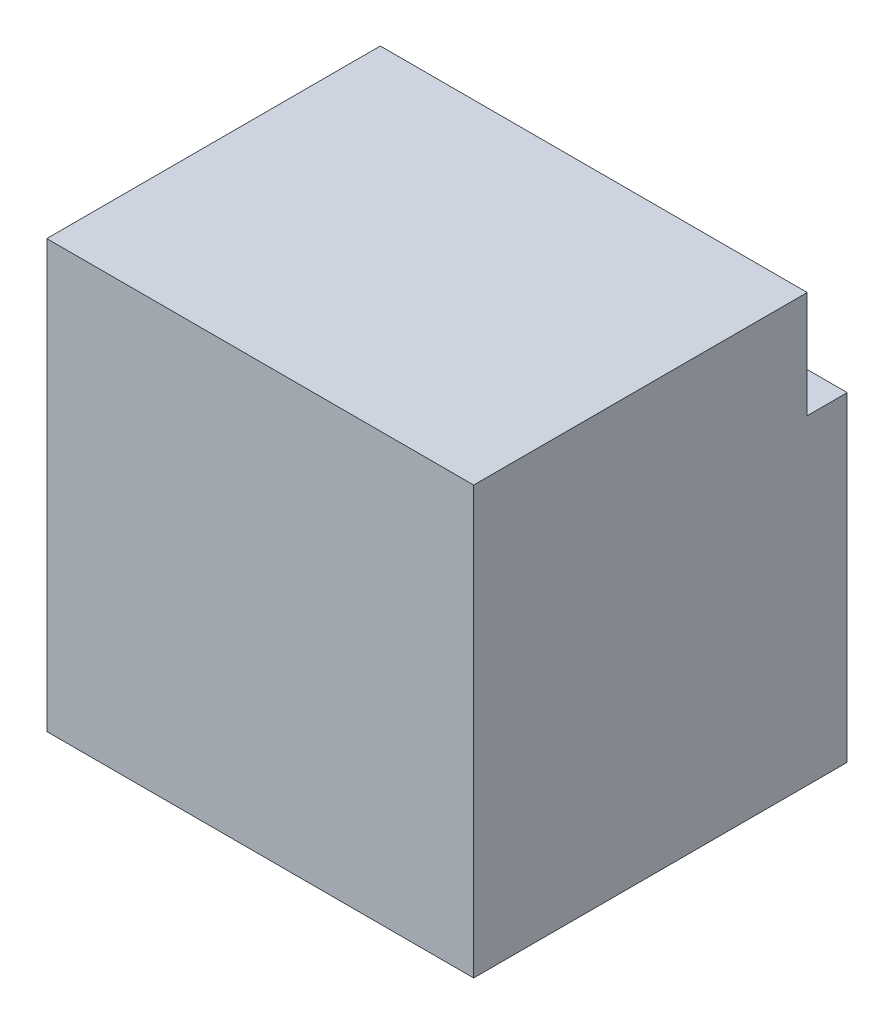
SolidWorks part; units mm, degrees
ref_plane "Ebene vorne" through (0, 0, 0) normal (0, 0, 1) x (1, 0, 0)
ref_plane "Ebene oben" through (0, 0, 0) normal (0, 1, 0) x (1, 0, 0)
ref_plane "Ebene rechts" through (0, 0, 0) normal (1, 0, 0) x (0, 0, -1)
sketch "Skizze1" plane through (0, 0, 0) normal (0, 0, 1) x (1, 0, 0)
  line L1 (-8, 8) -> (8, 8)
  line L2 (-8, 8) -> (-8, -8)
  line L3 (-8, -8) -> (8, -8)
  line L4 (8, 8) -> (8, -8)
  dimension "D1" = 16
  dimension "D2" = 16
  dimension "D3" = 8
  dimension "D4" = 8
extrude "Aufsatz-Linear austragen1" add sketch "Skizze1" along normal blind 14
sketch "Skizze2" plane through (0, -8, 0) normal (0, -1, 0) x (1, 0, 0)
  line L0 (-8, 0) -> (8, 0) construction
  line L1 (-5.5, 10) -> (5.5, 10)
  line L2 (-5.5, 10) -> (-5.5, 3)
  line L3 (-5.5, 3) -> (5.5, 3)
  line L4 (5.5, 10) -> (5.5, 3)
  dimension "D1" = 11
  dimension "D2" = 7
  dimension "D3" = 3
  dimension "D4" = 5.5
extrude "Schnitt-Linear austragen1" cut sketch "Skizze2" against normal blind 10
sketch "Skizze3" plane through (0, -8, 0) normal (0, -1, 0) x (1, 0, 0)
  line L0 (5.5, 10) -> (-5.5, 10) construction
  line L1 (-3.5, 12) -> (3.5, 12)
  line L2 (-3.5, 12) -> (-3.5, 10)
  line L3 (-3.5, 10) -> (3.5, 10)
  line L4 (3.5, 12) -> (3.5, 10)
  dimension "D1" = 2
  dimension "D2" = 7
  dimension "D3" = 3.5
extrude "Schnitt-Linear austragen2" cut sketch "Skizze3" against normal blind 10
sketch "Skizze4" plane through (0, -8, 0) normal (0, -1, 0) x (1, 0, 0)
  line L0 (3.5, 10) -> (3.5, 12) construction
  line L1 (4.1, 12.2) -> (6.1, 12.2)
  line L2 (4.1, 12.2) -> (4.1, 10.6)
  line L3 (4.1, 10.6) -> (6.1, 10.6)
  line L4 (6.1, 12.2) -> (6.1, 10.6)
  line L5 (-6.1, 12.2) -> (-4.1, 12.2)
  line L6 (-6.1, 12.2) -> (-6.1, 10.6)
  line L7 (-6.1, 10.6) -> (-4.1, 10.6)
  line L8 (-4.1, 12.2) -> (-4.1, 10.6)
  line L9 (5.5, 10) -> (3.5, 10) construction
  line L10 (-3.5, 12) -> (-3.5, 10) construction
  dimension "D1" = 2
  dimension "D2" = 1.6
  dimension "D3" = 2
  dimension "D4" = 1.6
  dimension "D5" = 0.6
  dimension "D6" = 0.6
  dimension "D7" = 0.6
extrude "Schnitt-Linear austragen3" cut sketch "Skizze4" against normal blind 15
sketch "Skizze5" plane through (0, 0, 0) normal (0, 0, -1) x (-1, 0, 0)
  line L0 (8, 8) -> (8, -8) construction
  line L1 (-8, 8) -> (8, 8)
  line L2 (-8, 8) -> (-8, 4)
  line L3 (-8, 4) -> (8, 4)
  line L4 (8, 8) -> (8, 4)
  dimension "D1" = 4
extrude "Schnitt-Linear austragen5" cut sketch "Skizze5" against normal blind 1.5
sketch "Skizze6" plane through (0, 0, 1.5) normal (0, 0, -1) x (-1, 0, 0)
  line L0 (8, 8) -> (-8, 8) construction
  line L1 (-6.5, 7.5) -> (-4.5, 7.5)
  line L2 (-6.5, 7.5) -> (-6.5, 5.5)
  line L3 (-6.5, 5.5) -> (-4.5, 5.5)
  line L4 (-4.5, 7.5) -> (-4.5, 5.5)
  line L5 (4.5, 7.5) -> (6.5, 7.5)
  line L6 (4.5, 7.5) -> (4.5, 5.5)
  line L7 (4.5, 5.5) -> (6.5, 5.5)
  line L8 (6.5, 7.5) -> (6.5, 5.5)
  line L9 (8, 4) -> (8, 8) construction
  line L10 (-8, 8) -> (-8, 4) construction
  dimension "D1" = 2
  dimension "D2" = 2
  dimension "D3" = 2
  dimension "D4" = 2
  dimension "D5" = 0.5
  dimension "D6" = 1.5
  dimension "D7" = 0.5
  dimension "D8" = 1.5
extrude "Schnitt-Linear austragen6" cut sketch "Skizze6" against normal blind 11.5
sketch "Skizze7" plane through (0, 0, 0) normal (0, 0, -1) x (-1, 0, 0)
  line L0 (-8, -8) -> (-8, 4) construction
  line L1 (-8, 1.2) -> (-7.7, 1.2)
  line L2 (-8, 1.2) -> (-8, 0)
  line L3 (-8, 0) -> (-7.7, 0)
  line L4 (-7.7, 1.2) -> (-7.7, 0)
  line L5 (8, 4) -> (8, -8) construction
  line L6 (8, 1.2) -> (7.7, 1.2)
  line L7 (8, 1.2) -> (8, 0)
  line L8 (8, 0) -> (7.7, 0)
  line L9 (7.7, 1.2) -> (7.7, 0)
  line L10 (8, -8) -> (-8, -8) construction
  circle A0 centre (-6.5, -2) radius 1.5
  circle A1 centre (6.5, -2) radius 1.5
  dimension "D7" = 3
  dimension "D8" = 3
  dimension "D9" = 6
  dimension "D1" = 1.2
  dimension "D2" = 1.2
  dimension "D3" = 0.3
  dimension "D4" = 0.3
  dimension "D5" = 8
  dimension "D6" = 8
  dimension "D10" = 6
